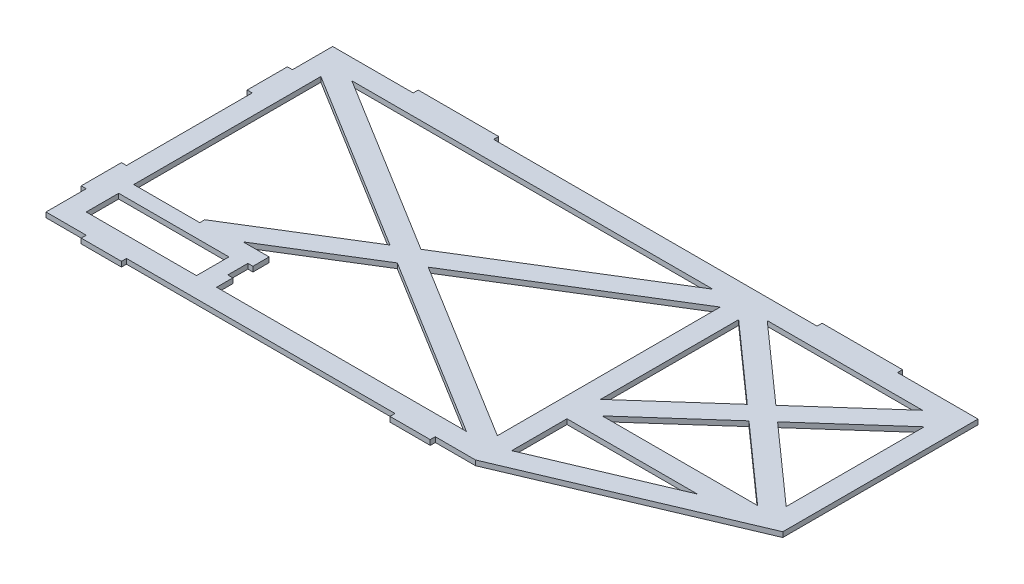
SolidWorks part; units mm, degrees
ref_plane "Front Plane" through (0, 0, 0) normal (0, 0, 1) x (1, 0, 0)
ref_plane "Top Plane" through (0, 0, 0) normal (0, 1, 0) x (1, 0, 0)
ref_plane "Right Plane" through (0, 0, 0) normal (1, 0, 0) x (0, 0, -1)
sketch "Sketch1" plane through (0, 0, 0) normal (0, 1, 0) x (1, 0, 0)
  line L0 (272.335, 4.8359) -> (136.0894, -52.9022)
  line L1 (-135.0556, 128.0728) -> (-84.2556, 128.0728)
  line L2 (-135.0556, 128.0728) -> (-135.0556, 102.6728)
  line L3 (-135.0556, -52.9022) -> (-109.6556, -52.9022)
  line L4 (201.0372, 54.7829) -> (250.0777, 11.1859)
  line L5 (136.0894, 128.0728) -> (170.735, 128.0728)
  line L6 (-56.5115, -7.0298) -> (-40.0596, -7.0298)
  line L7 (210.5946, 63.2794) -> (259.635, 19.6824)
  line L8 (272.335, 128.0728) -> (272.335, 4.8359)
  line L9 (142.4394, -1.5141) -> (142.4394, -36.4178)
  line L10 (151.9968, 115.3728) -> (250.0777, 115.3728)
  line L11 (142.4394, 106.8764) -> (142.4394, 19.6824)
  line L12 (151.9968, 11.1859) -> (250.0777, 11.1859)
  line L13 (259.635, 106.8764) -> (259.635, 19.6824)
  line L14 (142.4394, -36.4178) -> (224.8025, -1.5141)
  line L15 (142.4394, -1.5141) -> (224.8025, -1.5141)
  line L16 (-122.3556, 115.3728) -> (129.7394, -40.2022) construction
  line L17 (-110.2643, 115.3728) -> (117.6482, 115.3728)
  line L18 (-122.3556, 107.911) -> (-122.3556, -7.0298)
  line L19 (-40.0596, -40.2022) -> (117.6482, -40.2022)
  line L20 (129.7394, 107.911) -> (129.7394, -32.7403)
  line L21 (129.7394, 115.3728) -> (-122.3556, -40.2022) construction
  line L22 (142.4394, 115.3728) -> (259.635, 11.1859) construction
  line L23 (259.635, 115.3728) -> (142.4394, 11.1859) construction
  line L24 (-122.3556, 107.911) -> (-8.3993, 37.5853)
  line L25 (-110.2643, 115.3728) -> (3.6919, 45.0472)
  line L26 (-80.694, -7.0298) -> (-8.3993, 37.5853)
  line L27 (129.7394, 107.911) -> (15.7832, 37.5853)
  line L28 (142.4394, 106.8764) -> (191.4799, 63.2794)
  line L29 (151.9968, 115.3728) -> (201.0372, 71.7759)
  line L30 (151.9968, 11.1859) -> (201.0372, 54.7829)
  line L31 (250.0777, 115.3728) -> (201.0372, 71.7759)
  line L32 (15.7832, 37.5853) -> (129.7394, -32.7403)
  line L33 (3.6919, 45.0472) -> (117.6482, 115.3728)
  line L34 (3.6919, 30.1235) -> (117.6482, -40.2022)
  line L35 (3.6919, 30.1235) -> (-56.5115, -7.0298)
  line L36 (191.4799, 63.2794) -> (142.4394, 19.6824)
  line L37 (210.5946, 63.2794) -> (259.635, 106.8764)
  line L38 (-135.0556, 77.2728) -> (-135.0556, -2.1022)
  line L39 (-33.4556, 128.0728) -> (136.0894, 128.0728)
  line L40 (-40.0596, -17.266) -> (-43.2346, -17.266)
  line L41 (-40.0596, -40.2022) -> (-40.0596, -29.966)
  line L42 (-122.3556, -7.0298) -> (-122.3556, -10.2048)
  line L43 (-122.3556, -19.7298) -> (-52.7596, -19.7298)
  line L44 (-122.3556, -19.7298) -> (-122.3556, -40.2022)
  line L45 (-122.3556, -40.2022) -> (-52.7596, -40.2022)
  line L46 (-52.7596, -19.7298) -> (-52.7596, -40.2022)
  line L47 (-122.3556, -10.2048) -> (-80.694, -10.2048)
  line L48 (-80.694, -10.2048) -> (-80.694, -7.0298)
  line L49 (-43.2346, -17.266) -> (-43.2346, -29.966)
  line L50 (-43.2346, -29.966) -> (-40.0596, -29.966)
  line L51 (-40.0596, -17.266) -> (-40.0596, -7.0298)
  line L52 (136.0894, -52.9022) -> (136.0894, -128.7776) construction
  line L53 (-135.0556, 102.6728) -> (-138.2306, 102.6728)
  line L54 (-135.0556, -27.5022) -> (-135.0556, -52.9022)
  line L55 (-135.0556, 77.2728) -> (-138.2306, 77.2728)
  line L56 (-138.2306, 102.6728) -> (-138.2306, 77.2728)
  line L57 (-135.0556, -27.5022) -> (-138.2306, -27.5022)
  line L58 (-84.2556, -52.9022) -> (85.2894, -52.9022)
  line L59 (-135.0556, -2.1022) -> (-138.2306, -2.1022)
  line L60 (-138.2306, -27.5022) -> (-138.2306, -2.1022)
  line L61 (110.6894, -52.9022) -> (136.0894, -52.9022)
  line L62 (-109.6556, -52.9022) -> (-109.6556, -56.0772)
  line L63 (-109.6556, -56.0772) -> (-84.2556, -56.0772)
  line L64 (-84.2556, -52.9022) -> (-84.2556, -56.0772)
  line L65 (221.535, 128.0728) -> (272.335, 128.0728)
  line L66 (85.2894, -52.9022) -> (85.2894, -56.0772)
  line L67 (85.2894, -56.0772) -> (110.6894, -56.0772)
  line L68 (110.6894, -52.9022) -> (110.6894, -56.0772)
  line L71 (-84.2556, 128.0728) -> (-84.2556, 131.2478)
  line L72 (-84.2556, 131.2478) -> (-33.4556, 131.2478)
  line L73 (-33.4556, 128.0728) -> (-33.4556, 131.2478)
  line L75 (170.735, 128.0728) -> (170.735, 131.2478)
  line L76 (170.735, 131.2478) -> (221.535, 131.2478)
  line L77 (221.535, 128.0728) -> (221.535, 131.2478)
  dimension "D1" = 407.3906
  dimension "D2" = 271.145
  dimension "D3" = 180.975
  dimension "D4" = 12.7
  dimension "D5" = 12.7
  dimension "D6" = 12.7
  dimension "D7" = 41.6616
  dimension "D8" = 3.175
  dimension "D9" = 12.7
  dimension "D10" = 12.7
  dimension "D11" = 3.175
  dimension "D12" = 12.7
  dimension "D13" = 12.7
  dimension "D14" = 6.35
  dimension "D15" = 6.35
  dimension "D16" = 6.35
  dimension "D17" = 6.35
  dimension "D18" = 6.35
  dimension "D19" = 6.35
  dimension "D20" = 6.35
  dimension "D21" = 6.35
  dimension "D22" = 147.9748
  dimension "D23" = 12.7
  dimension "D24" = 25.4
  dimension "D25" = 25.4
  dimension "D26" = 3.175
  dimension "D27" = 3.175
  dimension "D28" = 25.4
  dimension "D29" = 25.4
  dimension "D30" = 25.4
  dimension "D31" = 25.4
  dimension "D32" = 25.4
  dimension "D33" = 25.4
  dimension "D34" = 3.175
  dimension "D35" = 3.175
  dimension "D36" = 50.8
  dimension "D37" = 50.8
  dimension "D38" = 50.8
  dimension "D39" = 50.8
  dimension "D40" = 3.175
  dimension "D41" = 3.175
extrude "Boss-Extrude1" add sketch "Sketch1" along normal blind 3.175
